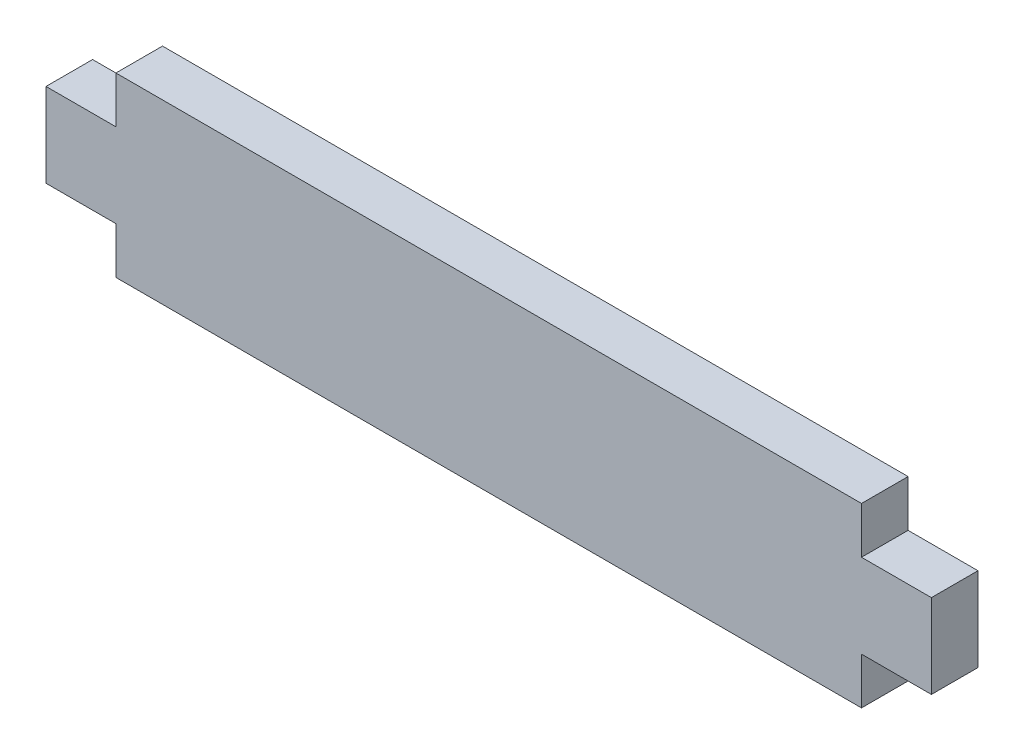
SolidWorks part; units mm, degrees
ref_plane "Front Plane" through (0, 0, 0) normal (0, 0, 1) x (1, 0, 0)
ref_plane "Top Plane" through (0, 0, 0) normal (0, 1, 0) x (1, 0, 0)
ref_plane "Right Plane" through (0, 0, 0) normal (1, 0, 0) x (0, 0, -1)
sketch "Sketch2" plane through (0, 0, 0) normal (0, 0, 1) x (1, 0, 0)
  line L0 (0, -14) -> (0, -19)
  line L1 (0, 0) -> (-80, 0)
  line L2 (0, 0) -> (0, -5)
  line L3 (0, -19) -> (-80, -19)
  line L4 (-80, 0) -> (-80, -5)
  line L5 (0, -5) -> (7.5, -5)
  line L7 (0, -14) -> (7.5, -14)
  line L8 (7.5, -5) -> (7.5, -14)
  line L9 (-80, -5) -> (-87.5, -5)
  line L11 (-80, -14) -> (-87.5, -14)
  line L12 (-87.5, -5) -> (-87.5, -14)
  line L13 (-80, -14) -> (-80, -19)
  dimension "D1" = 80
  dimension "D2" = 19
  dimension "D3" = 5
  dimension "D4" = 5
  dimension "D5" = 7.5
  dimension "D6" = 7.5
  dimension "D7" = 5
  dimension "D8" = 5
extrude "Boss-Extrude1" add sketch "Sketch2" along normal blind 5
